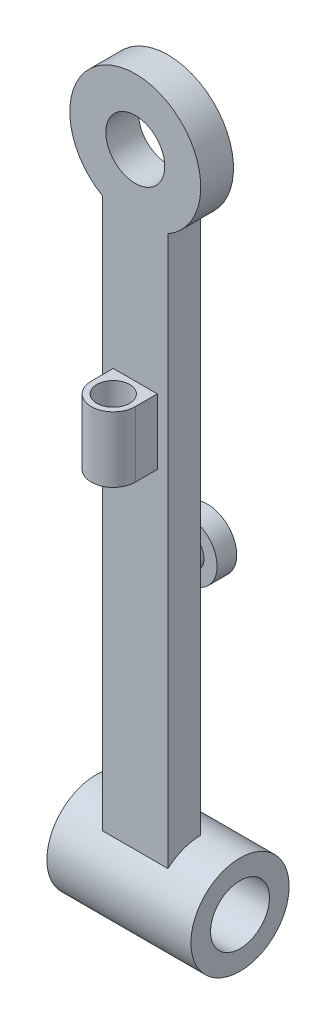
SolidWorks part; units mm, degrees
ref_plane "Front Plane" through (0, 0, 0) normal (0, 0, 1) x (1, 0, 0)
ref_plane "Top Plane" through (0, 0, 0) normal (0, 1, 0) x (1, 0, 0)
ref_plane "Right Plane" through (0, 0, 0) normal (1, 0, 0) x (0, 0, -1)
sketch "Sketch1" plane through (0, 0, 0) normal (0, 0, 1) x (1, 0, 0)
  line L2 (-5, 95) -> (-5, 0)
  line L4 (5, 95) -> (5, 0) construction
  line L5 (0, 0) -> (5, 0) construction
  line L6 (0, 0) -> (0, 99.1615) construction
  line L7 (-5, 0) -> (0, 0)
  line L8 (0, 0) -> (0, 99.1615)
  line L9 (0, 113.6626) -> (0, 108.1615)
  arc A0 (0, 108.1615) -> (0, 99.1615) centre (0, 103.6615) ccw
  arc A1 (0, 113.6626) -> (-5, 95) centre (0, 103.6615) ccw
  arc A3 (5, 95) -> (0, 113.6626) centre (0, 103.6615) ccw construction
  arc A4 (0, 99.1615) -> (0, 108.1615) centre (0, 103.6615) ccw construction
  dimension "D2" = 9
  dimension "D3" = 95
  dimension "D1" = 10
extrude "Boss-Extrude1" add sketch "Sketch1" along normal blind 5
sketch "Sketch3" plane through (-5, 0, 0) normal (-1, 0, 0) x (0, 0, 1)
  circle A0 centre (0, 5.4317) radius 7.5
  point P2 (-10, 15)
  point P3 (-3.9529, 11.7287)
  point P4 (-1.931, 7.2788)
  point P5 (0, 5.4317)
  dimension "D1" = 15
extrude "Boss-Extrude2" add sketch "Sketch3" along normal blind 6 and the other way blind 5
sketch "Sketch4" plane through (-11, 0, 0) normal (-1, 0, 0) x (0, 0, 1)
  circle A0 centre (0, 5.4317) radius 4.5
  dimension "D1" = 9
sketch "Sketch7" plane through (0, 0, 0) normal (0, 0, -1) x (-1, 0, 0)
  circle A0 centre (0, 46.7513) radius 2.5
  dimension "D1" = 5
extrude "Boss-Extrude7" add sketch "Sketch7" along normal blind 3
sketch "Sketch8" plane through (0, 0, -3) normal (0, 0, -1) x (-1, 0, 0)
  circle A2 centre (0, 46.7513) radius 4.5
  circle A3 centre (0, 46.7513) radius 4.5
  dimension "D1" = 2
extrude "Boss-Extrude8" add sketch "Sketch8" along normal blind 3
sketch "Sketch9" plane through (0, 0, 0) normal (0, 1, 0) x (1, 0, 0)
  line L0 (0, -2.75) -> (0, 2.75) construction
  line L1 (-3.3634, -8.3634) -> (-3.3634, -5)
  line L2 (-10.0011, -5) -> (0, -5) construction
  line L3 (3.3634, -8.3634) -> (3.3634, -5)
  line L4 (3.3634, -5) -> (-3.3634, -5)
  circle A0 centre (0, -8.3634) radius 2.5
  arc A1 (-3.3634, -8.3634) -> (3.3634, -8.3634) centre (0, -8.3634) ccw
  dimension "D1" = 5
extrude "Boss-Extrude9" add sketch "Sketch9" along normal blind 8 and the other way blind 2 from offset 65
mirror "Mirror1" about plane through (0, 0, 5) normal (-1, 0, 0) of "Boss-Extrude2", "Boss-Extrude1"
extrude "Cut-Extrude1" cut sketch "Sketch4" against normal through all
